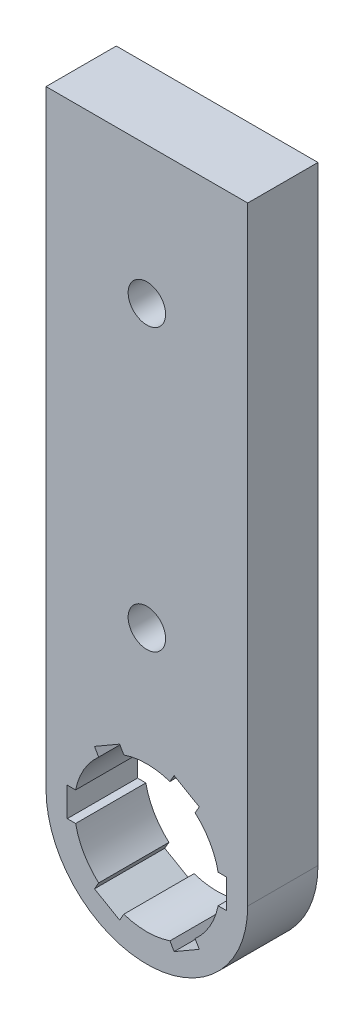
SolidWorks part; units mm, degrees
ref_plane "Front" through (0, 0, 0) normal (0, 0, 1) x (1, 0, 0)
ref_plane "Top" through (0, 0, 0) normal (0, 1, 0) x (1, 0, 0)
ref_plane "Right" through (0, 0, 0) normal (1, 0, 0) x (0, 0, -1)
sketch "Sketch1" plane through (0, 0, 0) normal (0, 0, 1) x (1, 0, 0)
  line L0 (0, -55) -> (0, 55) construction
  line L1 (-10.765, 32.5) -> (10.765, 32.5)
  line L2 (-10.765, 32.5) -> (-10.765, -32.5)
  line L4 (10.765, 32.5) -> (10.765, -32.5)
  line L5 (-10.765, 32.5) -> (10.765, -32.5) construction
  line L6 (-10.765, -32.5) -> (10.765, 32.5) construction
  line L8 (-10.765, -26.83) -> (10.765, -26.83) construction
  line L9 (0, -26.83) -> (0, 32.5) construction
  line L10 (-10.765, 2.835) -> (10.765, 2.835) construction
  arc A0 (-10.765, -32.5) -> (10.765, -32.5) centre (0, -32.5) ccw
  circle A1 centre (0, -32.5) radius 4.765
  circle A2 centre (0, 17.835) radius 2
  circle A4 centre (0, -12.165) radius 2
  point P0 (0, 0)
  point P12 (0, 2.835)
  dimension "D3" = 9.53
  dimension "D4" = 4
  dimension "D1" = 21.53
  dimension "D2" = 65
  dimension "D5" = 15
  dimension "D6" = 59.33
extrude "Boss-Extrude1" add sketch "Sketch1" along normal blind 7.5
sketch "Sketch3" plane through (0, 0, 7.5) normal (0, 0, 1) x (1, 0, 0)
  line L0 (-5.5923, -25.9138) -> (-2.9077, -24.3638)
  line L1 (-8.5, -34.05) -> (8.5, -34.05)
  line L2 (-8.5, -34.05) -> (-8.5, -30.95)
  line L3 (-8.5, -30.95) -> (8.5, -30.95)
  line L4 (8.5, -34.05) -> (8.5, -30.95)
  line L5 (-8.5, -34.05) -> (8.5, -30.95) construction
  line L6 (-8.5, -30.95) -> (8.5, -34.05) construction
  line L11 (-5.5923, -25.9138) -> (2.9077, -40.6362)
  line L12 (2.9077, -40.6362) -> (5.5923, -39.0862)
  line L13 (-2.9077, -24.3638) -> (5.5923, -39.0862)
  line L14 (2.9077, -24.3638) -> (5.5923, -25.9138)
  line L15 (2.9077, -24.3638) -> (-5.5923, -39.0862)
  line L16 (-5.5923, -39.0862) -> (-2.9077, -40.6362)
  line L17 (5.5923, -25.9138) -> (-2.9077, -40.6362)
  line L18 (8.5, -30.95) -> (8.5, -34.05)
  line L19 (8.5, -30.95) -> (-8.5, -30.95)
  line L20 (-8.5, -30.95) -> (-8.5, -34.05)
  line L21 (8.5, -34.05) -> (-8.5, -34.05)
  circle A0 centre (0, -32.5) radius 4.765 construction
  circle A2 centre (0, -32.5) radius 7.765
  dimension "D3" = 3
  dimension "D1" = 4
  dimension "D2" = 17
  dimension "D4" = 3.1
extrude "Cut-Extrude1" cut sketch "Sketch3" against normal up to next contours A2 L13 L0 L11 | A2 L3 L2 L1 | A2 L15 L16 L17 | A2 L11 L12 L13 | A2 L21 L4 L19 | A2 L17 L14 L15
